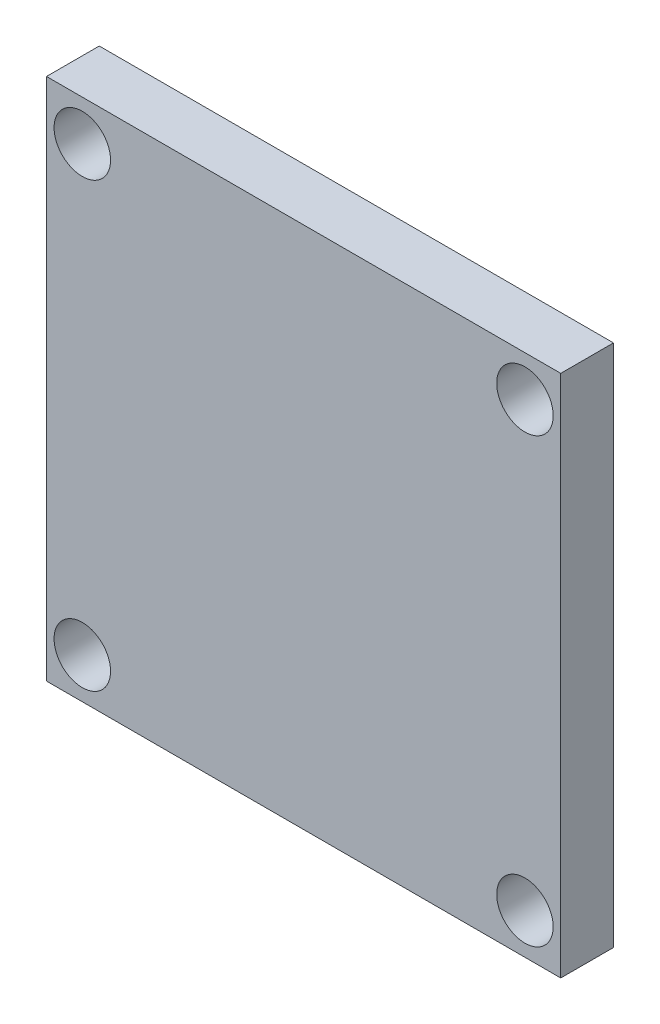
SolidWorks part; units mm, degrees
ref_plane "Front Plane" through (0, 0, 0) normal (0, 0, 1) x (1, 0, 0)
ref_plane "Top Plane" through (0, 0, 0) normal (0, 1, 0) x (1, 0, 0)
ref_plane "Right Plane" through (0, 0, 0) normal (1, 0, 0) x (0, 0, -1)
sketch "Sketch1" plane through (0, 0, 0) normal (0, 0, 1) x (1, 0, 0)
  line L1 (0, 0) -> (27.3, 0)
  line L2 (0, 0) -> (0, 27.8)
  line L3 (0, 27.8) -> (27.3, 27.8)
  line L4 (27.3, 0) -> (27.3, 27.8)
  dimension "D1" = 27.3
  dimension "D2" = 27.8
extrude "Boss-Extrude1" add sketch "Sketch1" along normal blind 2.8
sketch "Sketch2" plane through (0, 0, 2.8) normal (0, 0, 1) x (1, 0, 0)
  line L0 (0, 0) -> (27.3, 0) construction
  line L1 (1.9, 2.15) -> (25.4, 2.15) construction
  line L2 (1.9, 2.15) -> (1.9, 25.65) construction
  line L3 (1.9, 25.65) -> (25.4, 25.65) construction
  line L4 (25.4, 2.15) -> (25.4, 25.65) construction
  line L5 (0, 27.8) -> (0, 0) construction
  circle A0 centre (1.9, 25.65) radius 1.5
  circle A1 centre (25.4, 25.65) radius 1.5
  circle A2 centre (25.4, 2.15) radius 1.5
  circle A3 centre (1.9, 2.15) radius 1.5
  point P8 (0, 0)
  point P11 (0, 0)
  point P12 (0, 0)
  point P15 (13.65, 0)
  point P16 (13.65, 2.15)
  point P19 (0, 13.9)
  point P20 (1.9, 13.9)
  dimension "D3" = 3
  dimension "D1" = 23.5
  dimension "D2" = 23.5
extrude "Cut-Extrude1" cut sketch "Sketch2" against normal through all
